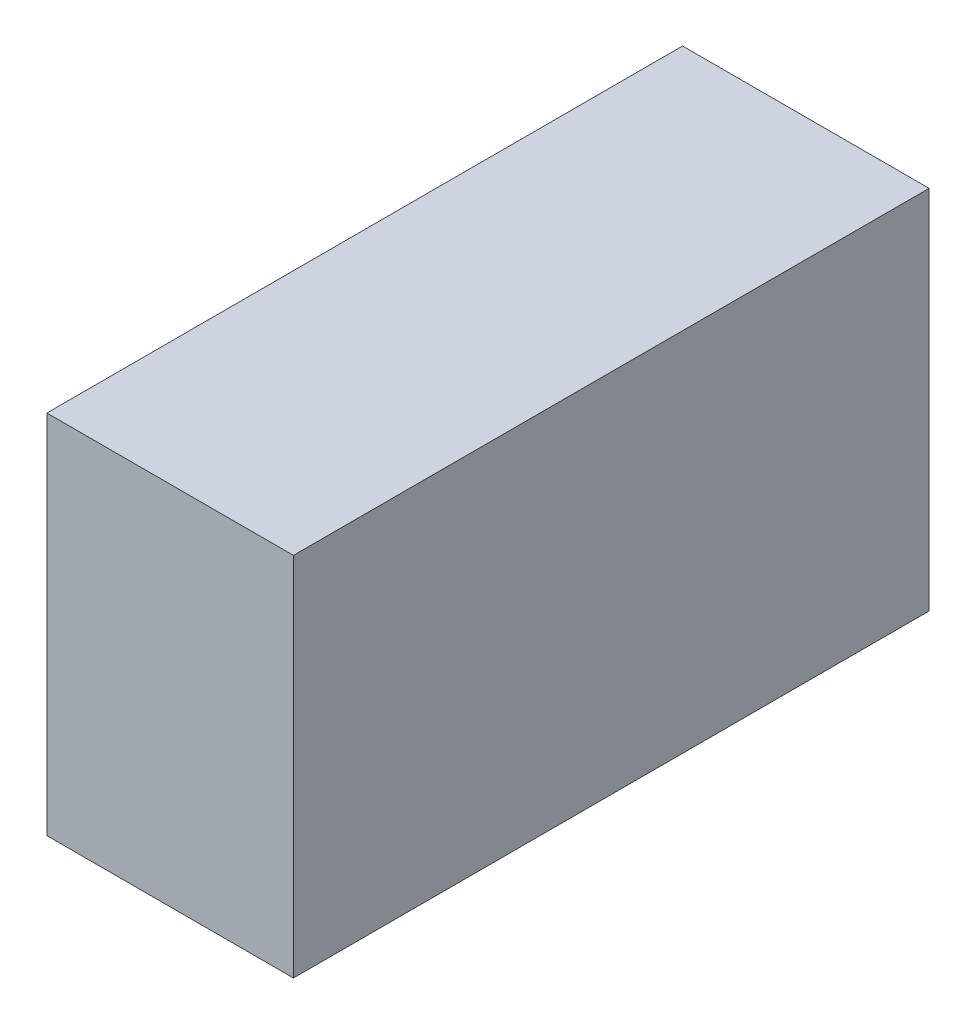
SolidWorks part; units mm, degrees
ref_plane "Alzado" through (0, 0, 0) normal (0, 0, 1) x (1, 0, 0)
ref_plane "Planta" through (0, 0, 0) normal (0, 1, 0) x (1, 0, 0)
ref_plane "Vista lateral" through (0, 0, 0) normal (1, 0, 0) x (0, 0, -1)
sketch "Croquis1" plane through (0, 0, 0) normal (0, 0, 1) x (1, 0, 0)
  line L1 (0, 0) -> (64, 0)
  line L2 (0, 0) -> (0, 95)
  line L3 (0, 95) -> (64, 95)
  line L4 (64, 0) -> (64, 95)
  dimension "D1" = 95
  dimension "D2" = 64
extrude "Saliente-Extruir1" add sketch "Croquis1" along normal blind 165
